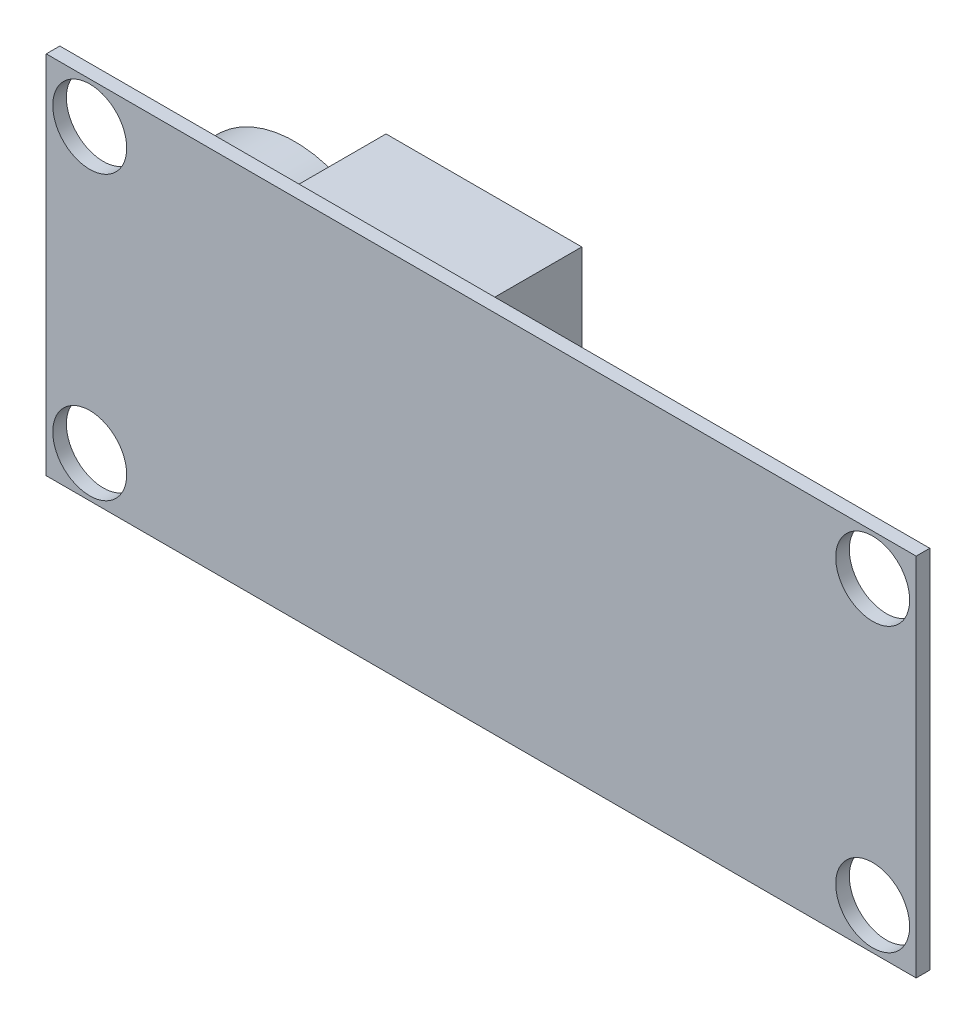
SolidWorks part; units mm, degrees
ref_plane "Front Plane" through (0, 0, 0) normal (0, 0, 1) x (1, 0, 0)
ref_plane "Top Plane" through (0, 0, 0) normal (0, 1, 0) x (1, 0, 0)
ref_plane "Right Plane" through (0, 0, 0) normal (1, 0, 0) x (0, 0, -1)
sketch "Sketch1" plane through (0, 0, 0) normal (0, 0, 1) x (1, 0, 0)
  line L1 (0, 0) -> (50.8, 0)
  line L2 (0, 0) -> (0, 21.336)
  line L3 (0, 21.336) -> (50.8, 21.336)
  line L4 (50.8, 0) -> (50.8, 21.336)
  dimension "D1" = 50.8
  dimension "D2" = 21.336
extrude "Boss-Extrude1" add sketch "Sketch1" along normal blind 0.7937
sketch "Sketch2" plane through (0, 0, 0.7937) normal (0, 0, 1) x (1, 0, 0)
  line L0 (0, 21.336) -> (0, 0) construction
  line L1 (50.8, 0) -> (50.8, 21.336) construction
  line L2 (50.8, 21.336) -> (0, 21.336) construction
  circle A0 centre (2.54, 18.923) radius 2.159
  circle A1 centre (2.54, 2.413) radius 2.159
  circle A2 centre (48.26, 2.413) radius 2.159
  circle A3 centre (48.26, 18.923) radius 2.159
  point P12 (2.54, 2.8475)
  point P15 (2.54, 18.923)
  dimension "D1" = 4.318
  dimension "D9" = 4.318
  dimension "D10" = 4.318
  dimension "D11" = 4.318
  dimension "D2" = 45.72
  dimension "D3" = 45.72
  dimension "D4" = 16.51
  dimension "D5" = 16.51
  dimension "D6" = 2.54
  dimension "D7" = 2.54
  dimension "D8" = 2.413
extrude "Cut-Extrude1" cut sketch "Sketch2" against normal through all
sketch "Sketch3" plane through (0, 0, 0) normal (0, 0, -1) x (-1, 0, 0)
  line L0 (-50.8, 21.336) -> (0, 21.336) construction
  line L1 (-24.13, 20.066) -> (-12.7, 20.066)
  line L2 (-24.13, 20.066) -> (-24.13, 14.986)
  line L3 (-24.13, 14.986) -> (-12.7, 14.986)
  line L4 (-12.7, 20.066) -> (-12.7, 14.986)
  line L5 (-24.13, 6.35) -> (-12.7, 6.35)
  line L6 (-24.13, 6.35) -> (-24.13, 1.27)
  line L7 (-24.13, 1.27) -> (-12.7, 1.27)
  line L8 (-12.7, 6.35) -> (-12.7, 1.27)
  line L9 (0, 0) -> (-50.8, 0) construction
  line L10 (0, 21.336) -> (0, 0) construction
  circle A0 centre (-7.3771, 10.668) radius 6.35
  point P10 (-7.3771, 11.3814)
  point P17 (0, 10.668)
  point P18 (-7.3771, 10.668)
  point P19 (-12.6713, 6.3876)
  point P20 (-12.8591, 14.4603)
  dimension "D3" = 12.7
  dimension "D1" = 1.27
  dimension "D2" = 1.27
  dimension "D4" = 7.3771
  dimension "D5" = 5.08
  dimension "D6" = 5.08
  dimension "D7" = 11.43
  dimension "D8" = 11.43
  dimension "D9" = 12.7
  dimension "D10" = 12.7
extrude "Boss-Extrude2" add sketch "Sketch3" along normal blind 6.35
sketch "Sketch4" plane through (24.13, 0, 0) normal (1, 0, 0) x (0, 0, -1)
  line L0 (6.35, 4.318) -> (6.35, 17.018) construction
  line L1 (0, 0) -> (0, 21.336) construction
  circle A0 centre (3.2271, 10.668) radius 3.048
  point P2 (3.2271, 10.668)
  point P7 (0, 10.668)
  dimension "D1" = 6.096
  dimension "D2" = 3.1229
extrude "Boss-Extrude3" add sketch "Sketch4" against normal blind 10.16 separate body
